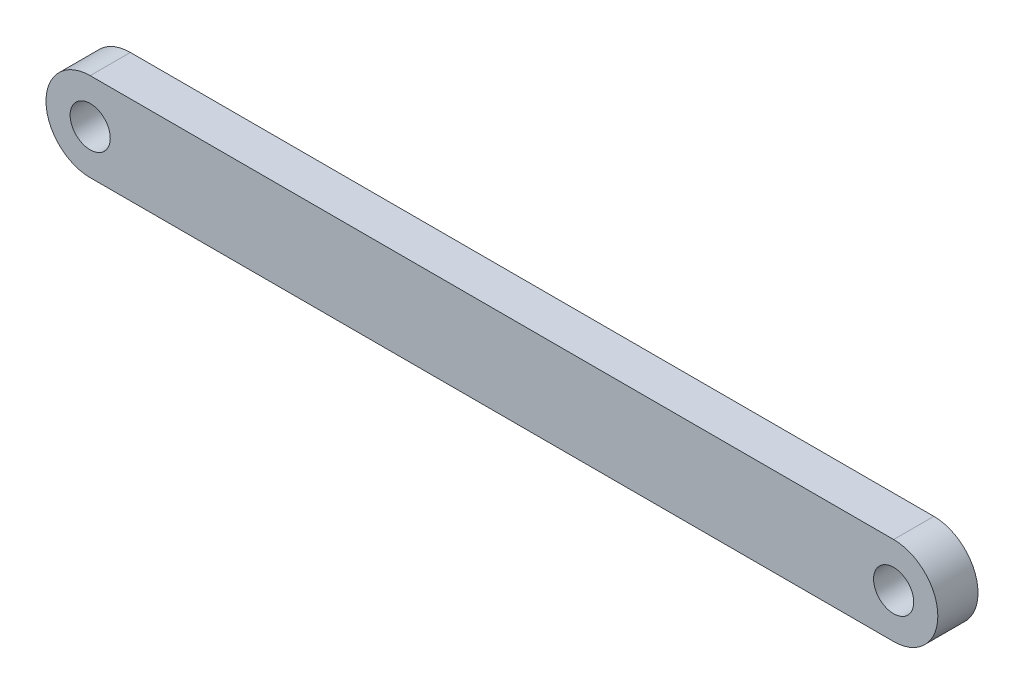
SolidWorks part; units mm, degrees
ref_plane "Front Plane" through (0, 0, 0) normal (0, 0, 1) x (1, 0, 0)
ref_plane "Top Plane" through (0, 0, 0) normal (0, 1, 0) x (1, 0, 0)
ref_plane "Right Plane" through (0, 0, 0) normal (1, 0, 0) x (0, 0, -1)
sketch "Sketch1" plane through (0, 0, 0) normal (0, 0, 1) x (1, 0, 0)
  line L0 (0, 0) -> (0, 27.1578) construction
  line L1 (-63.5, 6.985) -> (63.5, 6.985)
  line L3 (-63.5, -6.985) -> (63.5, -6.985)
  line L5 (-63.5, 6.985) -> (63.5, -6.985) construction
  line L6 (-63.5, -6.985) -> (63.5, 6.985) construction
  arc A0 (63.5, 6.985) -> (63.5, -6.985) centre (63.5, 0) cw
  arc A1 (-63.5, 6.985) -> (-63.5, -6.985) centre (-63.5, 0) ccw
  point P0 (0, 0)
  dimension "D1" = 127
  dimension "D2" = 13.97
extrude "Boss-Extrude1" add sketch "Sketch1" along normal blind 6.35
sketch "Sketch2" plane through (0, 0, 6.35) normal (0, 0, 1) x (1, 0, 0)
  circle A0 centre (63.5, 0) radius 3.175
  circle A1 centre (-63.5, 0) radius 3.175
  dimension "D1" = 6.35
extrude "Cut-Extrude1" cut sketch "Sketch2" against normal through all both
scale "Scale1" scale about centroid uniform scaling yes scale factor 4
